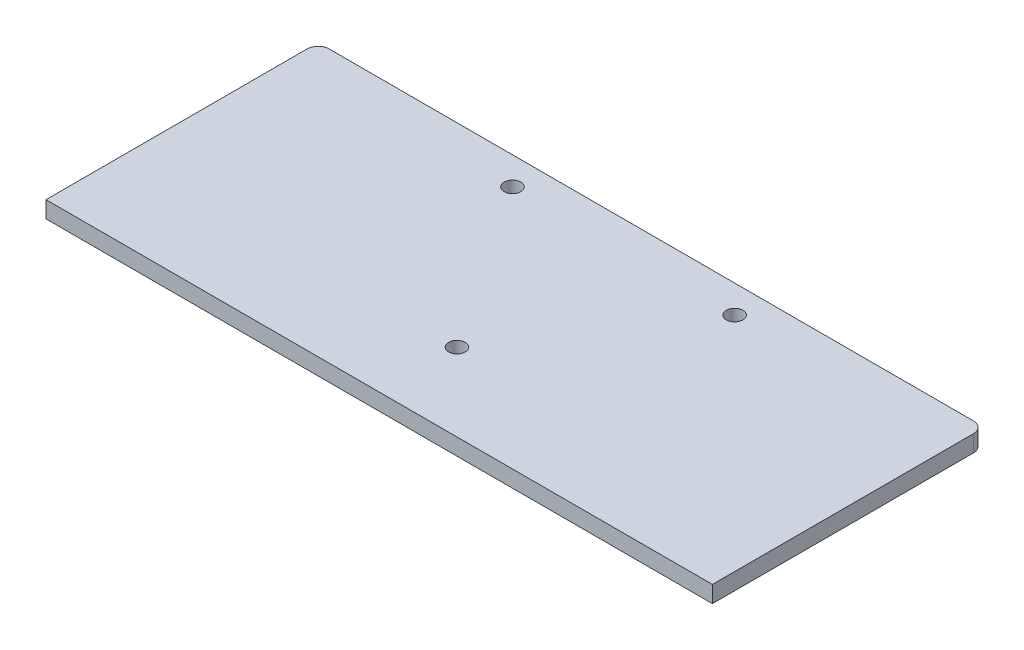
SolidWorks part; units mm, degrees
ref_plane "前视基准面" through (0, 0, 0) normal (0, 0, 1) x (1, 0, 0)
ref_plane "上视基准面" through (0, 0, 0) normal (0, 1, 0) x (1, 0, 0)
ref_plane "右视基准面" through (0, 0, 0) normal (1, 0, 0) x (0, 0, -1)
sketch "草图1" plane through (0, 0, 0) normal (0, 1, 0) x (1, 0, 0)
  line L1 (-35.2816, 21.8846) -> (84.7184, 21.8846)
  line L2 (-35.2816, 21.8846) -> (-35.2816, -27.1154)
  line L3 (-35.2816, -27.1154) -> (84.7184, -27.1154)
  line L4 (84.7184, 21.8846) -> (84.7184, -27.1154)
  dimension "D1" = 49
  dimension "D2" = 120
extrude "凸台-拉伸1" add sketch "草图1" along normal blind 3
sketch "草图2" plane through (0, 3, 0) normal (0, 1, 0) x (1, 0, 0)
  line L0 (-35.2816, 21.8846) -> (-35.2816, -27.1154) construction
  line L1 (84.7184, -27.1154) -> (84.7184, 21.8846) construction
  line L2 (84.7184, 21.8846) -> (-35.2816, 21.8846) construction
  circle A0 centre (4.7184, 16.8846) radius 1.5
  circle A1 centre (44.7184, 16.8846) radius 1.5
  circle A2 centre (24.7184, -13.1154) radius 1.5
  dimension "D1" = 3
  dimension "D2" = 3
  dimension "D3" = 3
  dimension "D4" = 40
  dimension "D5" = 40
  dimension "D6" = 30
  dimension "D7" = 20
  dimension "D8" = 5
  dimension "D9" = 5
extrude "切除-拉伸1" cut sketch "草图2" against normal blind 3
fillet "圆角1" radius 2 2 edges at (84.7184, 1.5, -21.8846) (-35.2816, 1.5, -21.8846)
